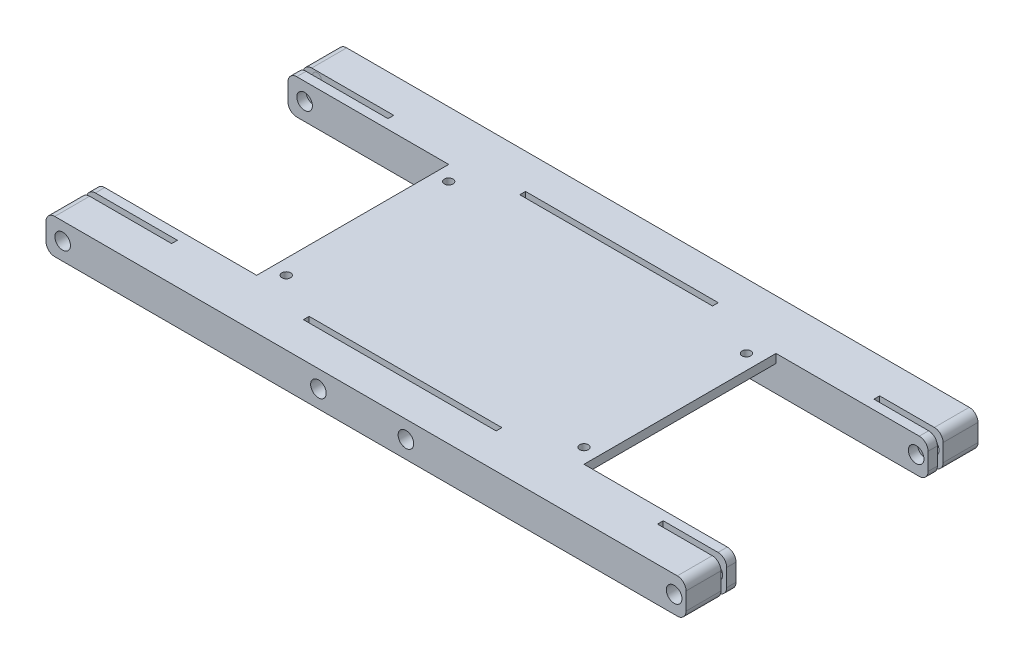
SolidWorks part; units mm, degrees
ref_plane "Front Plane" through (0, 0, 0) normal (0, 0, 1) x (1, 0, 0)
ref_plane "Top Plane" through (0, 0, 0) normal (0, 1, 0) x (1, 0, 0)
ref_plane "Right Plane" through (0, 0, 0) normal (1, 0, 0) x (0, 0, -1)
sketch "Sketch1" plane through (0, 0, 0) normal (0, 0, 1) x (1, 0, 0)
  line L0 (109.8741, 43.7425) -> (110.0523, 43.8945)
  line L1 (-103.9477, 43.8945) -> (110.0523, 43.8945)
  line L2 (-106.9477, 40.8945) -> (-106.9477, 34.8945)
  line L3 (-103.9477, 31.8945) -> (110.0523, 31.8945)
  line L4 (113.0523, 40.8945) -> (113.0523, 34.8945)
  arc A0 (-103.9477, 43.8945) -> (-106.9477, 40.8945) centre (-103.9477, 40.8945) ccw
  arc A1 (-106.9477, 34.8945) -> (-103.9477, 31.8945) centre (-103.9477, 34.8945) ccw
  arc A2 (110.0523, 31.8945) -> (113.0523, 34.8945) centre (110.0523, 34.8945) ccw
  arc A3 (110.0523, 43.8945) -> (113.0523, 40.8945) centre (110.0523, 40.8945) cw
  circle A4 centre (-102.1259, 37.8955) radius 1.6
  circle A5 centre (-102.1259, 41.8955) radius 1.5
  circle A6 centre (-102.1259, 33.8955) radius 1.5
  circle A7 centre (109.8742, 37.8918) radius 1.5
  circle A8 centre (-12.1259, 37.8955) radius 1.5
  circle A9 centre (17.8741, 37.8955) radius 1.5
  point P6 (-106.9477, 43.8955)
  point P11 (113.0523, 31.8945)
  point P14 (113.0523, 43.8945)
  dimension "D3" = 3
  dimension "D6" = 3.2
  dimension "D5" = 3
  dimension "D8" = 3
  dimension "D10" = 3
  dimension "D12" = 3
  dimension "D14" = 3
  dimension "D1" = 220
  dimension "D2" = 12
  dimension "D4" = 4
  dimension "D7" = 4
  dimension "D9" = 6
  dimension "D11" = 90
  dimension "D13" = 30
extrude "Boss-Extrude3" add sketch "Sketch1" along normal blind 3.2
pattern_linear "LPattern2" count 2 spacing 6.8 along (0, 0, 1) of bodies 103
ref_plane "Plane1" through (-103.9477, 43.8945, 3.2) normal (1, 0, 0) x (0, 0, -1)
sketch "Sketch4" plane through (0, 0, 3.2) normal (0, 0, 1) x (1, 0, 0)
  line L0 (3.0523, 31.8945) -> (3.0523, 63.7871) construction
  line L1 (-103.9477, 31.8945) -> (110.0523, 31.8945) construction
  line L2 (-103.9477, 43.8945) -> (110.0523, 43.8945) construction
  line L3 (3.0523, 43.8945) -> (7.6623, 43.8945)
  line L4 (3.0523, 43.8945) -> (-1.5577, 43.8945)
  dimension "D1" = 4.61
  dimension "D2" = 4.61
sketch "Sketch5" plane through (0, 0, 3.2) normal (0, 0, 1) x (1, 0, 0)
  line L0 (7.6623, 43.8945) -> (7.6623, 31.8945)
  line L1 (-103.9477, 31.8945) -> (110.0523, 31.8945) construction
  line L2 (-1.5577, 43.8945) -> (-1.5577, 31.8945)
  line L3 (-1.5577, 31.8945) -> (7.6623, 31.8945)
sketch "Sketch9" plane through (0, 0, 3.2) normal (0, 0, 1) x (1, 0, 0)
  line L1 (-1.5577, 43.8945) -> (7.6623, 43.8945)
  line L2 (7.6623, 43.8945) -> (7.6623, 31.8945)
  line L3 (7.6623, 31.8945) -> (-1.5577, 31.8945)
  line L4 (-1.5577, 43.8945) -> (-1.5577, 31.8945)
extrude "Boss-Extrude5" add sketch "Sketch9" along normal blind 3.7
sketch "Sketch11" plane through (0, 0, 3.2) normal (0, 0, 1) x (1, 0, 0)
  line L1 (30.7949, 43.8945) -> (91.2254, 43.8945)
  line L2 (-103.9477, 43.8945) -> (110.0523, 43.8945) construction
  line L3 (-79.6965, 43.8945) -> (-79.7588, 43.8945)
  line L4 (-79.7588, 43.8945) -> (-79.7588, 31.8945)
  line L5 (-103.9477, 31.8945) -> (110.0523, 31.8945) construction
  line L6 (-79.7588, 31.8945) -> (-23.8197, 31.8945)
  line L7 (-23.8197, 31.8945) -> (-23.8197, 43.8945)
  line L8 (-23.8197, 43.8945) -> (-79.6965, 43.8945)
  line L9 (30.7949, 43.8945) -> (30.7949, 31.8945)
  line L10 (30.7949, 31.8945) -> (91.2254, 31.8945)
  line L11 (91.2254, 43.8945) -> (91.2254, 31.8945)
extrude "Boss-Extrude6" add sketch "Sketch11" along normal blind 3.7
pattern_linear "LPattern3" count 2 spacing 76 along (0, 0, 1) of bodies 108
sketch "Sketch13" plane through (0, 43.8945, 0) normal (0, 1, 0) x (1, 0, 0)
  line L0 (-103.9477, -10) -> (110.0523, -10) construction
  line L1 (-51.7024, -10) -> (60.7994, -10)
  line L2 (-51.7024, -10) -> (-51.7024, -76)
  line L3 (-51.7024, -76) -> (60.7994, -76)
  line L4 (60.7994, -10) -> (60.7994, -76)
  line L5 (-103.9477, -76) -> (110.0523, -76) construction
extrude "Boss-Extrude8" add sketch "Sketch13" against normal blind 3 contours L2 L3 L4 L1
sketch "Sketch14" plane through (0, 43.8945, 0) normal (0, 1, 0) x (1, 0, 0)
  line L0 (-51.7024, -10) -> (-51.7024, -76) construction
  line L1 (-103.9477, -10) -> (-51.7024, -10) construction
  line L2 (-103.9477, -76) -> (-51.7024, -76) construction
  line L3 (60.7994, -10) -> (60.7994, -76) construction
  circle A0 centre (-46.6224, -15.08) radius 1.5
  circle A1 centre (55.7194, -15.08) radius 1.5
  circle A2 centre (55.7194, -70.92) radius 1.5
  circle A3 centre (-46.6224, -70.92) radius 1.5
  dimension "D1" = 5.08
  dimension "D2" = 5.08
  dimension "D3" = 3
  dimension "D4" = 3
  dimension "D5" = 3
  dimension "D6" = 3
  dimension "D7" = 5.08
  dimension "D8" = 5.08
  dimension "D9" = 5.08
extrude "Cut-Extrude2" cut sketch "Sketch14" against normal blind 4.318 contours A1 | A2 | A0 | A3
sketch "Sketch22" plane through (0, 40.8945, 0) normal (0, -1, 0) x (1, 0, 0)
  line L0 (-51.7024, 76) -> (60.7994, 76) construction
  line L1 (-39.3253, 76) -> (-34.1504, 76)
  line L2 (-39.3253, 76) -> (-39.3253, 65.7826)
  line L3 (-39.3253, 65.7826) -> (-34.1504, 65.7826)
  line L4 (-34.1504, 76) -> (-34.1504, 65.7826)
  line L5 (-24.0853, 76) -> (-24.0853, 65.7826)
  line L6 (-24.0853, 76) -> (-18.9104, 76)
  line L7 (-18.9104, 76) -> (-18.9104, 65.7826)
  line L8 (-24.0853, 65.7826) -> (-18.9104, 65.7826)
  line L9 (-8.8453, 76) -> (-8.8453, 65.7826)
  line L10 (-8.8453, 76) -> (-3.6704, 76)
  line L11 (-3.6704, 76) -> (-3.6704, 65.7826)
  line L12 (-8.8453, 65.7826) -> (-3.6704, 65.7826)
  line L13 (6.3947, 76) -> (6.3947, 65.7826)
  line L14 (6.3947, 76) -> (11.5696, 76)
  line L15 (11.5696, 76) -> (11.5696, 65.7826)
  line L16 (6.3947, 65.7826) -> (11.5696, 65.7826)
  line L17 (21.6347, 76) -> (21.6347, 65.7826)
  line L18 (21.6347, 76) -> (26.8096, 76)
  line L19 (26.8096, 76) -> (26.8096, 65.7826)
  line L20 (21.6347, 65.7826) -> (26.8096, 65.7826)
  line L21 (36.8747, 76) -> (36.8747, 65.7826)
  line L22 (36.8747, 76) -> (42.0496, 76)
  line L23 (42.0496, 76) -> (42.0496, 65.7826)
  line L24 (36.8747, 65.7826) -> (42.0496, 65.7826)
  line L25 (-24.0853, 20.12) -> (-24.0853, 9.9026)
  line L26 (-24.0853, 20.12) -> (-18.9104, 20.12)
  line L27 (-18.9104, 20.12) -> (-18.9104, 9.9026)
  line L28 (-24.0853, 9.9026) -> (-18.9104, 9.9026)
  line L29 (-8.8453, 20.12) -> (-8.8453, 9.9026)
  line L30 (-8.8453, 20.12) -> (-3.6704, 20.12)
  line L31 (-3.6704, 20.12) -> (-3.6704, 9.9026)
  line L32 (-8.8453, 9.9026) -> (-3.6704, 9.9026)
  line L33 (6.3947, 20.12) -> (6.3947, 9.9026)
  line L34 (6.3947, 20.12) -> (11.5696, 20.12)
  line L35 (11.5696, 20.12) -> (11.5696, 9.9026)
  line L36 (6.3947, 9.9026) -> (11.5696, 9.9026)
  line L37 (21.6347, 20.12) -> (21.6347, 9.9026)
  line L38 (21.6347, 20.12) -> (26.8096, 20.12)
  line L39 (26.8096, 20.12) -> (26.8096, 9.9026)
  line L40 (21.6347, 9.9026) -> (26.8096, 9.9026)
  line L41 (36.8747, 20.12) -> (36.8747, 9.9026)
  line L42 (36.8747, 20.12) -> (42.0496, 20.12)
  line L43 (42.0496, 20.12) -> (42.0496, 9.9026)
  line L44 (36.8747, 9.9026) -> (42.0496, 9.9026)
  line L45 (-39.3253, 20.12) -> (-39.3253, 9.9026)
  line L46 (-39.3253, 20.12) -> (-34.1504, 20.12)
  line L47 (-34.1504, 20.12) -> (-34.1504, 9.9026)
  line L48 (-39.3253, 9.9026) -> (-34.1504, 9.9026)
  dimension "D1" = 6
  dimension "D2" = 2
extrude "Boss-Extrude9" add sketch "Sketch22" along normal blind 4.318
sketch "Sketch31" plane through (0, 0, 0) normal (0, 0, -1) x (-1, 0, 0)
  line L0 (-113.0523, 34.8945) -> (-113.0523, 40.8945)
  line L1 (103.9477, 43.8945) -> (-110.0523, 43.8945)
  line L2 (106.9477, 40.8945) -> (106.9477, 34.8945)
  line L3 (103.9477, 31.8945) -> (-110.0523, 31.8945)
  arc A0 (-113.0523, 40.8945) -> (-110.0523, 43.8945) centre (-110.0523, 40.8945) cw
  arc A1 (103.9477, 43.8945) -> (106.9477, 40.8945) centre (103.9477, 40.8945) cw
  arc A2 (106.9477, 34.8945) -> (103.9477, 31.8945) centre (103.9477, 34.8945) cw
  arc A3 (-110.0523, 31.8945) -> (-113.0523, 34.8945) centre (-110.0523, 34.8945) cw
  circle A4 centre (-109.8742, 37.8918) radius 1.5
  circle A5 centre (-17.8741, 37.8955) radius 1.5
  circle A6 centre (12.1259, 37.8955) radius 1.5
  circle A7 centre (102.1259, 37.8955) radius 1.6
  circle A8 centre (102.1259, 41.8955) radius 1.5
  circle A9 centre (102.1259, 33.8955) radius 1.5
extrude "Boss-Extrude10" add sketch "Sketch31" along normal blind 12.446 and the other way blind 4.826
sketch "Sketch34" plane through (0, 0, 86) normal (0, 0, 1) x (1, 0, 0)
  line L0 (-106.9477, 34.8945) -> (-106.9477, 40.8945)
  line L1 (-103.9477, 43.8945) -> (110.0523, 43.8945)
  line L2 (113.0523, 40.8945) -> (113.0523, 34.8945)
  line L3 (110.0523, 31.8945) -> (-103.9477, 31.8945)
  arc A0 (-106.9477, 40.8945) -> (-103.9477, 43.8945) centre (-103.9477, 40.8945) cw
  arc A1 (110.0523, 43.8945) -> (113.0523, 40.8945) centre (110.0523, 40.8945) cw
  arc A2 (113.0523, 34.8945) -> (110.0523, 31.8945) centre (110.0523, 34.8945) cw
  arc A3 (-103.9477, 31.8945) -> (-106.9477, 34.8945) centre (-103.9477, 34.8945) cw
  circle A4 centre (-102.1259, 41.8955) radius 1.5
  circle A5 centre (-102.1259, 37.8955) radius 1.6
  circle A6 centre (-102.1259, 33.8955) radius 1.5
  circle A7 centre (-12.1259, 37.8955) radius 1.5
  circle A8 centre (17.8741, 37.8955) radius 1.5
  circle A9 centre (109.8742, 37.8918) radius 1.5
extrude "Boss-Extrude13" add sketch "Sketch34" along normal blind 12.446 and the other way blind 4.826
scale "Scale1" bodies to scale 118 scale about centroid uniform scaling yes scale factor 1.5
sketch "Sketch36" plane through (0, 0, -40.1701) normal (0, 0, -1) x (-1, 0, 0)
  line L1 (-167.6363, 42.0213) -> (-167.6363, 33.0213)
  line L2 (-163.1363, 28.5213) -> (157.8637, 28.5213)
  line L3 (162.3637, 33.0213) -> (162.3637, 42.0213)
  line L4 (157.8637, 46.5213) -> (-163.1363, 46.5213)
  arc A0 (-167.6363, 33.0213) -> (-163.1363, 28.5213) centre (-163.1363, 33.0213) ccw
  arc A1 (157.8637, 28.5213) -> (162.3637, 33.0213) centre (157.8637, 33.0213) ccw
  arc A2 (162.3637, 42.0213) -> (157.8637, 46.5213) centre (157.8637, 42.0213) ccw
  arc A3 (-163.1363, 46.5213) -> (-167.6363, 42.0213) centre (-163.1363, 42.0213) ccw
  circle A4 centre (-162.8691, 37.5173) radius 2.25
  circle A5 centre (-24.869, 37.5228) radius 2.25
  circle A6 centre (20.131, 37.5228) radius 2.25
  circle A7 centre (155.131, 43.5228) radius 2.25
  circle A8 centre (155.131, 37.5228) radius 2.4
  circle A9 centre (155.131, 31.5228) radius 2.25
extrude "Cut-Extrude3" cut sketch "Sketch36" against normal blind 7.91
sketch "Sketch39" plane through (0, 0, 126.1679) normal (0, 0, 1) x (1, 0, 0)
  line L0 (167.6363, 42.0213) -> (167.6363, 33.0213)
  line L1 (163.1363, 46.5213) -> (-157.8637, 46.5213)
  line L2 (-162.3637, 42.0213) -> (-162.3637, 33.0213)
  line L3 (-157.8637, 28.5213) -> (163.1363, 28.5213)
  circle A0 centre (-155.131, 43.5228) radius 2.25
  circle A1 centre (-155.131, 37.5228) radius 2.4
  circle A2 centre (-155.131, 31.5228) radius 2.25
  circle A3 centre (-20.131, 37.5228) radius 2.25
  circle A4 centre (24.869, 37.5228) radius 2.25
  circle A5 centre (162.8691, 37.5173) radius 2.25
  arc A6 (167.6363, 42.0213) -> (163.1363, 46.5213) centre (163.1363, 42.0213) ccw
  arc A7 (-157.8637, 46.5213) -> (-162.3637, 42.0213) centre (-157.8637, 42.0213) ccw
  arc A8 (-162.3637, 33.0213) -> (-157.8637, 28.5213) centre (-157.8637, 33.0213) ccw construction
  arc A9 (-162.3637, 33.0213) -> (-157.8637, 28.5213) centre (-157.8637, 33.0213) ccw
  arc A10 (163.1363, 28.5213) -> (167.6363, 33.0213) centre (163.1363, 33.0213) ccw
extrude "Cut-Extrude4" cut sketch "Sketch39" against normal blind 7.91
sketch "Sketch42" plane through (-121.5805, 0, 0) normal (-1, 0, 0) x (0, 0, 1)
  line L1 (-14.2621, 46.5213) -> (-11.3011, 46.5213)
  line L2 (-14.2621, 46.5213) -> (-14.2621, 28.5213)
  line L3 (-14.2621, 28.5213) -> (-11.3011, 28.5213)
  line L4 (-11.3011, 46.5213) -> (-11.3011, 28.5213)
  line L5 (97.2989, 46.5213) -> (100.2599, 46.5213)
  line L6 (97.2989, 46.5213) -> (97.2989, 28.5213)
  line L7 (97.2989, 28.5213) -> (100.2599, 28.5213)
  line L8 (100.2599, 46.5213) -> (100.2599, 28.5213)
extrude "Cut-Extrude5" cut sketch "Sketch42" against normal blind 6
sketch "Sketch44" plane through (-37.6718, 0, 0) normal (1, 0, 0) x (0, 0, -1)
  line L1 (11.3011, 46.5213) -> (14.2621, 46.5213)
  line L2 (11.3011, 46.5213) -> (11.3011, 28.5213)
  line L3 (11.3011, 28.5213) -> (14.2621, 28.5213)
  line L4 (14.2621, 46.5213) -> (14.2621, 28.5213)
  line L5 (-100.2599, 46.5213) -> (-97.2989, 46.5213)
  line L6 (-100.2599, 46.5213) -> (-100.2599, 28.5213)
  line L7 (-100.2599, 28.5213) -> (-97.2989, 28.5213)
  line L8 (-97.2989, 46.5213) -> (-97.2989, 28.5213)
extrude "Cut-Extrude6" cut sketch "Sketch44" against normal blind 5
sketch "Sketch45" plane through (-4.2787, 0, 0) normal (-1, 0, 0) x (0, 0, 1)
  line L1 (-14.2621, 46.5213) -> (-11.3011, 46.5213)
  line L2 (-14.2621, 46.5213) -> (-14.2621, 28.5213)
  line L3 (-14.2621, 28.5213) -> (-11.3011, 28.5213)
  line L4 (-11.3011, 46.5213) -> (-11.3011, 28.5213)
  line L5 (97.2989, 46.5213) -> (100.2599, 46.5213)
  line L6 (97.2989, 46.5213) -> (97.2989, 28.5213)
  line L7 (97.2989, 28.5213) -> (100.2599, 28.5213)
  line L8 (100.2599, 46.5213) -> (100.2599, 28.5213)
extrude "Cut-Extrude7" cut sketch "Sketch45" against normal blind 56
sketch "Sketch49" plane through (0, 0, -32.2601) normal (0, 0, -1) x (-1, 0, 0)
  circle A0 centre (-161.4954, 37.4793) radius 4.025
  dimension "D1" = 8.05
extrude "Cut-Extrude9" cut sketch "Sketch49" against normal blind 164
sketch "Sketch51" plane through (0, 0, 118.2579) normal (0, 0, 1) x (1, 0, 0)
  circle A0 centre (-155.131, 43.5228) radius 2.25
  circle A1 centre (-155.131, 31.5228) radius 2.25
extrude "Boss-Extrude14" add sketch "Sketch51" against normal blind 18
sketch "Sketch53" plane through (0, 0, 97.2989) normal (0, 0, 1) x (1, 0, 0)
  circle A0 centre (-155.131, 43.5228) radius 2.25
  circle A1 centre (-155.131, 31.5228) radius 2.25
extrude "Boss-Extrude15" add sketch "Sketch53" against normal blind 4.8
sketch "Sketch57" plane through (0, 0, -32.2601) normal (0, 0, -1) x (-1, 0, 0)
  circle A0 centre (155.131, 43.5228) radius 2.25
  circle A1 centre (155.131, 31.5228) radius 2.25
extrude "Boss-Extrude16" add sketch "Sketch57" against normal blind 18
sketch "Sketch58" plane through (0, 0, -11.3011) normal (0, 0, -1) x (-1, 0, 0)
  circle A0 centre (155.131, 43.5228) radius 2.25
  circle A1 centre (155.131, 31.5228) radius 2.25
extrude "Boss-Extrude17" add sketch "Sketch58" against normal blind 4.8
sketch "Sketch59" plane through (0, 0, -32.2601) normal (0, 0, -1) x (-1, 0, 0)
  circle A1 centre (153.7823, 37.5228) radius 4.025
  dimension "D1" = 8.05
extrude "Cut-Extrude11" cut sketch "Sketch59" against normal blind 182.8
sketch "Sketch62" plane through (0, 0, 92.4989) normal (0, 0, -1) x (-1, 0, 0)
  circle A2 centre (-23.2082, 37.4984) radius 4.025
  circle A3 centre (21.8977, 37.5046) radius 4.025
  dimension "D1" = 8.05
  dimension "D2" = 8.05
extrude "Cut-Extrude12" cut sketch "Sketch62" along normal blind 184.8 and the other way blind 76
sketch "Sketch65" plane through (-42.6718, 0, 0) normal (1, 0, 0) x (0, 0, -1)
  line L1 (11.3011, 46.5213) -> (14.2621, 46.5213)
  line L2 (11.3011, 46.5213) -> (11.3011, 28.5213)
  line L3 (11.3011, 28.5213) -> (14.2621, 28.5213)
  line L4 (14.2621, 46.5213) -> (14.2621, 28.5213)
  line L5 (-97.2989, 28.5213) -> (-100.2599, 28.5213)
  line L6 (-97.2989, 28.5213) -> (-97.2989, 46.5213)
  line L7 (-97.2989, 46.5213) -> (-100.2599, 46.5213)
  line L8 (-100.2599, 28.5213) -> (-100.2599, 46.5213)
extrude "Cut-Extrude13" cut sketch "Sketch65" against normal blind 5
